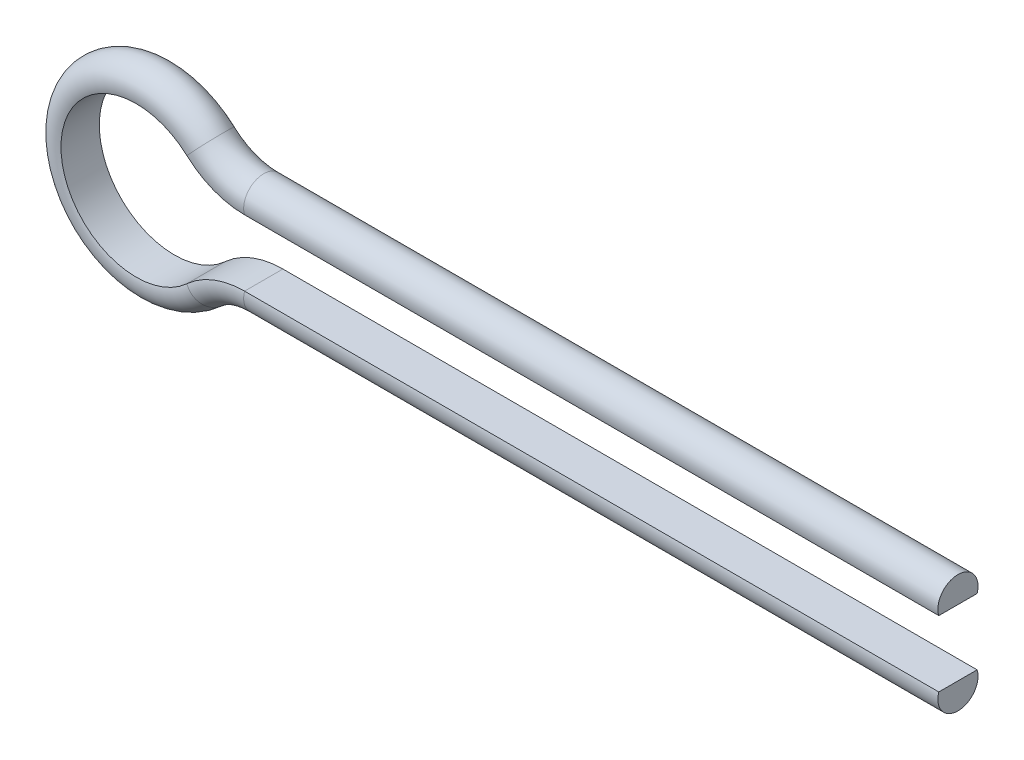
SolidWorks part; units mm, degrees
ref_plane "Front Plane" through (0, 0, 0) normal (0, 0, 1) x (1, 0, 0)
ref_plane "Top Plane" through (0, 0, 0) normal (0, 1, 0) x (1, 0, 0)
ref_plane "Right Plane" through (0, 0, 0) normal (1, 0, 0) x (0, 0, -1)
sketch "Sketch1" plane through (0, 0, 0) normal (0, 0, 1) x (1, 0, 0)
  line L0 (13.5069, 3.5) -> (100, 3.5)
  line L5 (13.5069, -6) -> (100, -6)
  arc A0 (6.7535, 6.125) -> (6.7535, -8.625) centre (0, -1.25) ccw
  arc A2 (6.7535, 6.125) -> (13.5069, 3.5) centre (13.5069, 13.5) ccw
  arc A3 (6.7535, -8.625) -> (13.5069, -6) centre (13.5069, -16) cw
  dimension "D2" = 6.7535
  dimension "D3" = 3.5
  dimension "D4" = 100
  dimension "D1" = 10
ref_plane "Plane1" through (100, 0, 0) normal (1, 0, 0) x (0, 0, -1)
sketch "Sketch3" plane through (100, 0, 0) normal (1, 0, 0) x (0, 0, -1)
  line L0 (0, 8.75) -> (0, -11.25) construction
  line L1 (-2.3871, 2.8663) -> (2.3871, 2.8663)
  arc A0 (2.3871, 2.8663) -> (-2.3871, 2.8663) centre (0, 3.609) ccw
  dimension "D1" = 5
  dimension "D2" = 2.3871
  dimension "D3" = 2.8663
sweep "Sweep2" add profiles "Sketch3" path "Sketch1"
